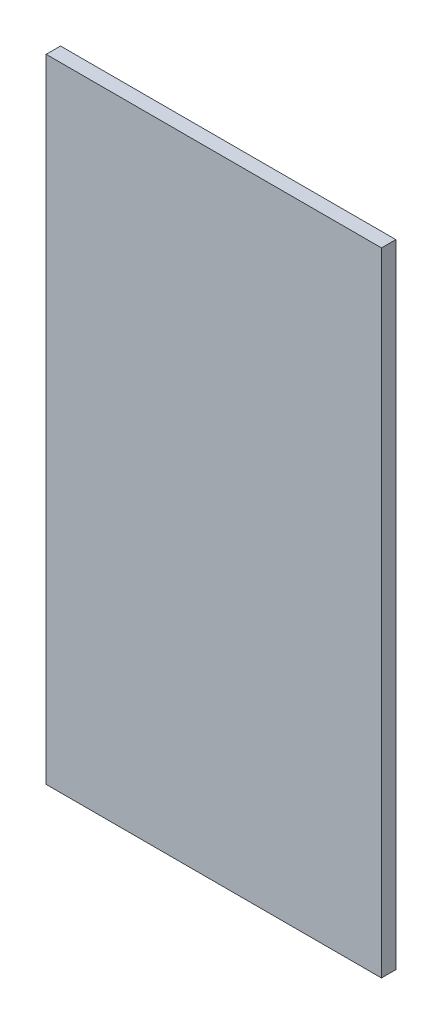
SolidWorks part; units mm, degrees
material "Teak"
ref_plane "Front Plane" through (0, 0, 0) normal (0, 0, 1) x (1, 0, 0)
ref_plane "Top Plane" through (0, 0, 0) normal (0, 1, 0) x (1, 0, 0)
ref_plane "Right Plane" through (0, 0, 0) normal (1, 0, 0) x (0, 0, -1)
sketch "Sketch1" plane through (0, 0, 0) normal (0, 0, 1) x (1, 0, 0)
  line L1 (0, 0) -> (420, 0)
  line L2 (0, 0) -> (0, 792)
  line L3 (0, 792) -> (420, 792)
  line L4 (420, 0) -> (420, 792)
  dimension "D1" = 420
  dimension "D2" = 792
extrude "Boss-Extrude1" add sketch "Sketch1" along normal blind 18
